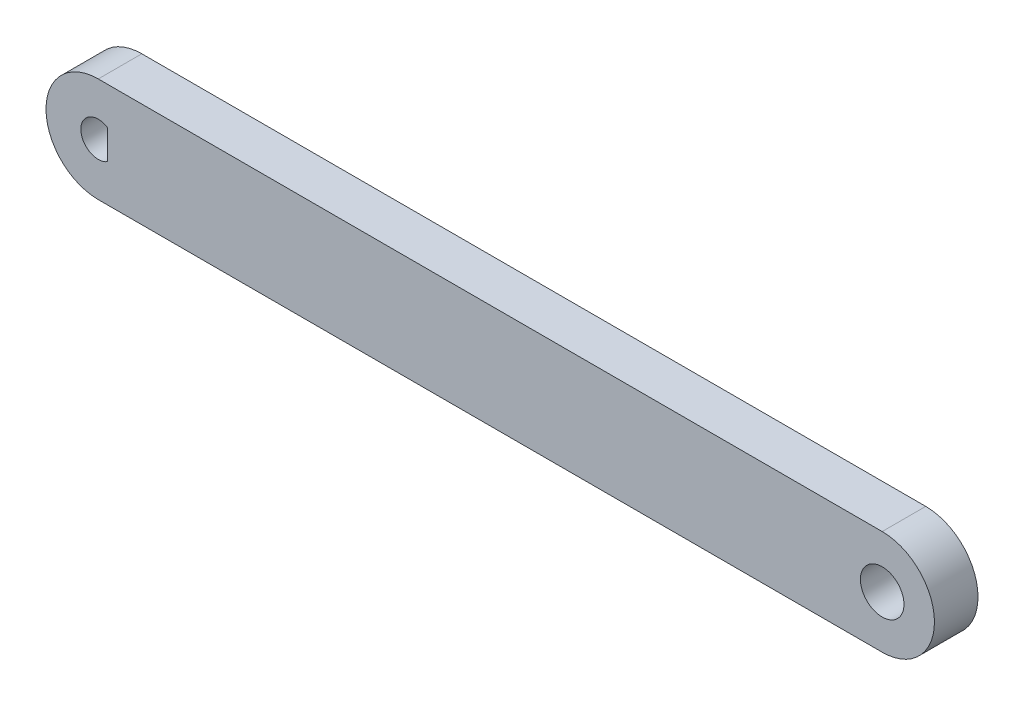
SolidWorks part; units mm, degrees
ref_plane "Alzado" through (0, 0, 0) normal (0, 0, 1) x (1, 0, 0)
ref_plane "Planta" through (0, 0, 0) normal (0, 1, 0) x (1, 0, 0)
ref_plane "Vista lateral" through (0, 0, 0) normal (1, 0, 0) x (0, 0, -1)
sketch "Croquis1" plane through (0, 0, 0) normal (0, 0, 1) x (1, 0, 0)
  line L0 (-45, 0) -> (45, 0) construction
  line L1 (-45, 6) -> (45, 6)
  line L2 (-45, -6) -> (45, -6)
  arc A0 (-45, 6) -> (-45, -6) centre (-45, 0) ccw
  arc A1 (45, -6) -> (45, 6) centre (45, 0) ccw
  circle A2 centre (45, 0) radius 2.5
  circle A3 centre (-45, 0) radius 2.5
  point P3 (0, 0)
  dimension "D2" = 6
  dimension "D3" = 5
  dimension "D4" = 5
  dimension "D1" = 90
extrude "Saliente-Extruir1" add sketch "Croquis1" along normal mid plane 5
sketch "Croquis3" plane through (0, 0, 2.5) normal (0, 0, 1) x (1, 0, 0)
  line L0 (-47, 0) -> (-43.9341, 0)
  line L1 (-43.9341, -1.6923) -> (-43.9341, 1.6923)
  line L2 (-45, -6) -> (45, -6)
  line L3 (45, 6) -> (-45, 6)
  line L4 (-45, -6) -> (45, -6)
  line L5 (45, 6) -> (-45, 6)
  circle A0 centre (-45, 0) radius 2
  arc A2 (-45, 6) -> (-45, -6) centre (-45, 0) ccw
  arc A3 (45, -6) -> (45, 6) centre (45, 0) ccw
  arc A4 (-45, 6) -> (-45, -6) centre (-45, 0) ccw
  arc A5 (45, -6) -> (45, 6) centre (45, 0) ccw
  circle M6 centre (-45, 0) radius 2.5
  dimension "D2" = 4
  dimension "3.5" = 3.0659
  dimension "D1" = 0
extrude "Saliente-Extruir7" add sketch "Croquis3" against normal through all contours A0 M6 | L1 A0
